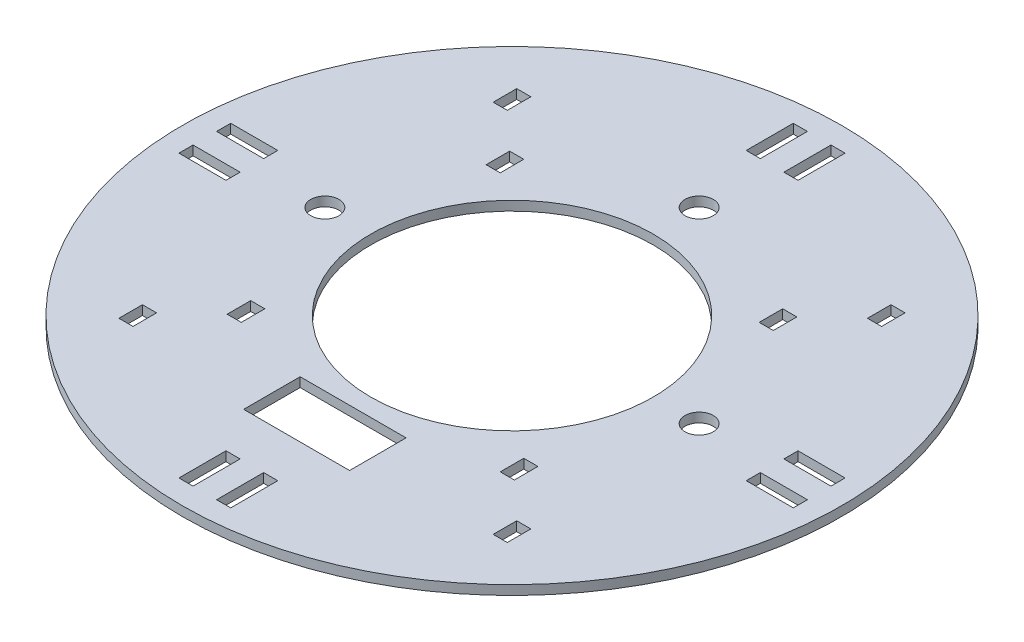
SolidWorks part; units mm, degrees
material "Thornel Mat VMA"
ref_plane "Front Plane" through (0, 0, 0) normal (0, 0, 1) x (1, 0, 0)
ref_plane "Top Plane" through (0, 0, 0) normal (0, 1, 0) x (1, 0, 0)
ref_plane "Right Plane" through (0, 0, 0) normal (1, 0, 0) x (0, 0, -1)
sketch "Sketch1" plane through (0, 0, 0) normal (0, 1, 0) x (1, 0, 0)
  line L0 (-49.4975, 49.4975) -> (-30, 30) construction
  line L1 (-52.2487, 5) -> (-67.2487, 5) construction
  line L2 (-67.2487, 5) -> (-67.2487, -5) construction
  line L3 (-67.2487, -5) -> (-52.2487, -5) construction
  line L4 (-52.2487, -5) -> (-52.2487, 5) construction
  line L5 (-30, -30) -> (30, 30) construction
  line L6 (-30, 30) -> (30, -30) construction
  line L7 (-30, 30) -> (-28, 30)
  line L8 (-30, 30) -> (-30, 25)
  line L9 (-30, 25) -> (-28, 25)
  line L10 (-28, 30) -> (-28, 25)
  line L11 (30, 30) -> (28, 30)
  line L12 (30, 30) -> (30, 25)
  line L13 (30, 25) -> (28, 25)
  line L14 (28, 30) -> (28, 25)
  line L15 (-30, -30) -> (-28, -30)
  line L16 (-30, -30) -> (-30, -25)
  line L17 (-30, -25) -> (-28, -25)
  line L18 (-28, -30) -> (-28, -25)
  line L19 (30, -30) -> (28, -30)
  line L20 (30, -30) -> (30, -25)
  line L21 (30, -25) -> (28, -25)
  line L22 (28, -30) -> (28, -25)
  line L23 (30, 30) -> (49.4975, 49.4975) construction
  line L24 (-49.4975, -49.4975) -> (-30, -30) construction
  line L25 (-30, -30) -> (-30, 30) construction
  line L26 (-30, 30) -> (30, 30) construction
  line L27 (30, 30) -> (30, -30) construction
  line L28 (30, -30) -> (30.057, -29.7836) construction
  line L29 (49.4975, -49.4975) -> (30, -30) construction
  line L30 (0, 49.4975) -> (0, 70) construction
  line L31 (-40.7487, 42.2487) -> (-38.7487, 42.2487)
  line L32 (-40.7487, 42.2487) -> (-40.7487, 37.2487)
  line L33 (-40.7487, 37.2487) -> (-38.7487, 37.2487)
  line L34 (-38.7487, 42.2487) -> (-38.7487, 37.2487)
  line L35 (-40.7487, 42.2487) -> (-38.7487, 37.2487) construction
  line L36 (-40.7487, 37.2487) -> (-38.7487, 42.2487) construction
  line L37 (38.7487, 42.2487) -> (40.7487, 42.2487)
  line L38 (38.7487, 42.2487) -> (38.7487, 37.2487)
  line L39 (38.7487, 37.2487) -> (40.7487, 37.2487)
  line L40 (40.7487, 42.2487) -> (40.7487, 37.2487)
  line L41 (38.7487, 42.2487) -> (40.7487, 37.2487) construction
  line L42 (38.7487, 37.2487) -> (40.7487, 42.2487) construction
  line L43 (38.7487, -37.2487) -> (40.7487, -37.2487)
  line L44 (38.7487, -37.2487) -> (38.7487, -42.2487)
  line L45 (38.7487, -42.2487) -> (40.7487, -42.2487)
  line L46 (40.7487, -37.2487) -> (40.7487, -42.2487)
  line L47 (38.7487, -37.2487) -> (40.7487, -42.2487) construction
  line L48 (38.7487, -42.2487) -> (40.7487, -37.2487) construction
  line L49 (-40.7487, -37.2487) -> (-38.7487, -37.2487)
  line L50 (-40.7487, -37.2487) -> (-40.7487, -42.2487)
  line L51 (-40.7487, -42.2487) -> (-38.7487, -42.2487)
  line L52 (-38.7487, -37.2487) -> (-38.7487, -42.2487)
  line L53 (-40.7487, -37.2487) -> (-38.7487, -42.2487) construction
  line L54 (-40.7487, -42.2487) -> (-38.7487, -37.2487) construction
  line L55 (-49.4975, 0) -> (-70, 0) construction
  line L56 (49.4975, 0) -> (70, 0) construction
  line L57 (0, -49.4975) -> (0, -70) construction
  line L58 (-49.4975, 0) -> (-30, 0) construction
  line L60 (-11.25, -33.7487) -> (11.25, -33.7487)
  line L61 (-11.25, -33.7487) -> (-11.25, -45.7487)
  line L62 (-11.25, -45.7487) -> (11.25, -45.7487)
  line L63 (-5, 52.2487) -> (5, 67.2487) construction
  line L64 (-5, 67.2487) -> (5, 52.2487) construction
  line L65 (-5, 52.2487) -> (5, 52.2487) construction
  line L66 (5, 52.2487) -> (5, 67.2487) construction
  line L67 (5, 67.2487) -> (-5, 67.2487) construction
  line L68 (-5, 67.2487) -> (-5, 52.2487) construction
  line L69 (52.2487, -5) -> (67.2487, 5) construction
  line L70 (52.2487, 5) -> (67.2487, -5) construction
  line L71 (52.2487, -5) -> (67.2487, -5) construction
  line L72 (67.2487, -5) -> (67.2487, 5) construction
  line L73 (67.2487, 5) -> (52.2487, 5) construction
  line L74 (52.2487, 5) -> (52.2487, -5) construction
  line L75 (-5, -52.2487) -> (5, -67.2487) construction
  line L76 (-5, -67.2487) -> (5, -52.2487) construction
  line L77 (-5, -52.2487) -> (5, -52.2487) construction
  line L78 (5, -52.2487) -> (5, -67.2487) construction
  line L79 (5, -67.2487) -> (-5, -67.2487) construction
  line L80 (-5, -67.2487) -> (-5, -52.2487) construction
  line L81 (-67.2487, 5) -> (-52.2487, -5) construction
  line L82 (-67.2487, -5) -> (-52.2487, 5) construction
  line L83 (-67.2487, 5) -> (-62.2487, 5)
  line L84 (-67.2487, 5) -> (-67.2487, 3)
  line L85 (-67.2487, 3) -> (-62.2487, 3)
  line L86 (-62.2487, 5) -> (-62.2487, 3)
  line L87 (-67.2487, -5) -> (-62.2487, -5)
  line L88 (-67.2487, -5) -> (-67.2487, -3)
  line L89 (-67.2487, -3) -> (-62.2487, -3)
  line L90 (-62.2487, -5) -> (-62.2487, -3)
  line L91 (-52.2487, -5) -> (-57.2487, -5)
  line L92 (-52.2487, -5) -> (-52.2487, -3)
  line L93 (-52.2487, -3) -> (-57.2487, -3)
  line L94 (-57.2487, -5) -> (-57.2487, -3)
  line L95 (-52.2487, 5) -> (-57.2487, 5)
  line L96 (-52.2487, 5) -> (-52.2487, 3)
  line L97 (-52.2487, 3) -> (-57.2487, 3)
  line L98 (-57.2487, 5) -> (-57.2487, 3)
  line L99 (-5, 67.2487) -> (-3, 67.2487)
  line L100 (-5, 67.2487) -> (-5, 62.2487)
  line L101 (-5, 62.2487) -> (-3, 62.2487)
  line L102 (-3, 67.2487) -> (-3, 62.2487)
  line L103 (-5, 52.2487) -> (-3, 52.2487)
  line L104 (-5, 52.2487) -> (-5, 57.2487)
  line L105 (-5, 57.2487) -> (-3, 57.2487)
  line L106 (-3, 52.2487) -> (-3, 57.2487)
  line L107 (5, 52.2487) -> (3, 52.2487)
  line L108 (5, 52.2487) -> (5, 57.2487)
  line L109 (5, 57.2487) -> (3, 57.2487)
  line L110 (3, 52.2487) -> (3, 57.2487)
  line L111 (5, 67.2487) -> (3, 67.2487)
  line L112 (5, 67.2487) -> (5, 62.2487)
  line L113 (5, 62.2487) -> (3, 62.2487)
  line L114 (3, 67.2487) -> (3, 62.2487)
  line L115 (52.2487, 5) -> (57.2487, 5)
  line L116 (52.2487, 5) -> (52.2487, 3)
  line L117 (52.2487, 3) -> (57.2487, 3)
  line L118 (57.2487, 5) -> (57.2487, 3)
  line L119 (52.2487, -5) -> (57.2487, -5)
  line L120 (52.2487, -5) -> (52.2487, -3)
  line L121 (52.2487, -3) -> (57.2487, -3)
  line L122 (57.2487, -5) -> (57.2487, -3)
  line L123 (67.2487, 5) -> (62.2487, 5)
  line L124 (67.2487, 5) -> (67.2487, 3)
  line L125 (67.2487, 3) -> (62.2487, 3)
  line L126 (62.2487, 5) -> (62.2487, 3)
  line L127 (67.2487, -5) -> (62.2487, -5)
  line L128 (67.2487, -5) -> (67.2487, -3)
  line L129 (67.2487, -3) -> (62.2487, -3)
  line L130 (62.2487, -5) -> (62.2487, -3)
  line L131 (-5, -52.2487) -> (-3, -52.2487)
  line L132 (-5, -52.2487) -> (-5, -57.2487)
  line L133 (-5, -57.2487) -> (-3, -57.2487)
  line L134 (-3, -52.2487) -> (-3, -57.2487)
  line L135 (5, -52.2487) -> (3, -52.2487)
  line L136 (5, -52.2487) -> (5, -57.2487)
  line L137 (5, -57.2487) -> (3, -57.2487)
  line L138 (3, -52.2487) -> (3, -57.2487)
  line L139 (5, -67.2487) -> (3, -67.2487)
  line L140 (5, -67.2487) -> (5, -62.2487)
  line L141 (5, -62.2487) -> (3, -62.2487)
  line L142 (3, -67.2487) -> (3, -62.2487)
  line L143 (-5, -67.2487) -> (-3, -67.2487)
  line L144 (-5, -67.2487) -> (-5, -62.2487)
  line L145 (-5, -62.2487) -> (-3, -62.2487)
  line L146 (-3, -67.2487) -> (-3, -62.2487)
  line L147 (0, 49.4975) -> (0, 30) construction
  line L148 (30, 0) -> (49.4975, 0) construction
  line L149 (0, -30) -> (0, -49.4975) construction
  line L150 (-49.4975, -49.4975) -> (-49.4975, 49.4975) construction
  line L151 (-49.4975, 49.4975) -> (49.4975, 49.4975) construction
  line L152 (49.4975, 49.4975) -> (49.4975, -49.4975) construction
  line L153 (49.4975, -49.4975) -> (-49.4975, -49.4975) construction
  line L154 (-30, -30) -> (30, -30) construction
  line L155 (-52.2487, 5) -> (-67.2487, 5) construction
  line L156 (11.25, -33.7487) -> (11.25, -45.7487)
  line L157 (-11.25, -33.7487) -> (11.25, -45.7487) construction
  line L158 (-11.25, -45.7487) -> (11.25, -33.7487) construction
  circle A0 centre (0, 0) radius 30
  circle A1 centre (0, 0) radius 70
  circle A2 centre (0, -39.7487) radius 3
  circle A3 centre (39.7487, 0) radius 3
  circle A4 centre (-39.7487, 0) radius 3
  circle A5 centre (0, 39.7487) radius 3
  point P20 (-39.7487, 39.7487)
  point P29 (39.7487, 39.7487)
  point P34 (39.7487, -39.7487)
  point P39 (-39.7487, -39.7487)
  point P52 (0, 59.7487)
  point P57 (59.7487, 0)
  point P62 (0, -59.7487)
  point P67 (-59.7487, 0)
  dimension "D1" = 60
  dimension "D2" = 140
  dimension "D65" = 6
  dimension "D66" = 6
  dimension "D67" = 6
  dimension "D68" = 6
  dimension "D3" = 60
  dimension "D4" = 60
  dimension "D5" = 5
  dimension "D6" = 2
  dimension "D7" = 5
  dimension "D8" = 2
  dimension "D9" = 2
  dimension "D10" = 5
  dimension "D11" = 2
  dimension "D12" = 5
  dimension "D13" = 5
  dimension "D14" = 2
  dimension "D15" = 5
  dimension "D16" = 2
  dimension "D17" = 2
  dimension "D18" = 5
  dimension "D19" = 2
  dimension "D20" = 5
  dimension "D21" = 20.5025
  dimension "D22" = 15
  dimension "D23" = 10
  dimension "D24" = 20.5025
  dimension "D25" = 15
  dimension "D26" = 10
  dimension "D27" = 20.5025
  dimension "D28" = 15
  dimension "D29" = 10
  dimension "D30" = 20.5025
  dimension "D31" = 15
  dimension "D32" = 10
  dimension "D33" = 5
  dimension "D34" = 2
  dimension "D35" = 5
  dimension "D36" = 2
  dimension "D37" = 5
  dimension "D38" = 2
  dimension "D39" = 5
  dimension "D40" = 5
  dimension "D41" = 5
  dimension "D42" = 5
  dimension "D43" = 5
  dimension "D44" = 2
  dimension "D45" = 2
  dimension "D46" = 2
  dimension "D47" = 2
  dimension "D48" = 5
  dimension "D49" = 5
  dimension "D50" = 5
  dimension "D51" = 5
  dimension "D52" = 2
  dimension "D53" = 2
  dimension "D54" = 2
  dimension "D55" = 2
  dimension "D56" = 2
  dimension "D57" = 5
  dimension "D58" = 5
  dimension "D59" = 2
  dimension "D60" = 2
  dimension "D61" = 2
  dimension "D62" = 5
  dimension "D63" = 5
  dimension "D64" = 2
  dimension "D69" = 19.4975
  dimension "D70" = 22.5
  dimension "D71" = 12
extrude "Yükseklik-Ekstrüzyon1" add sketch "Sketch1" along normal blind 2 contours A1 A5 A4 A3 L60 L156 L62 L61 L146 L143 L144 L145 L131 L134 L133 L132 L115 L118 L117 L116 L114 L111 L112 L113 L99 L102 L101 L100 L98 L95 L96 L97 L83 L86 L85 L84 L43 L46 L45
sketch "Sketch2" plane through (0, 2, 0) normal (0, 1, 0) x (1, 0, 0)
  line L0 (-52.2487, 5) -> (-52.2487, 21.5478)
  line L1 (-52.2487, 21.5478) -> (-52.2487, -8.4522)
  dimension "D1" = 30
sketch "Sketch3" plane through (0, 2, 0) normal (0, 1, 0) x (1, 0, 0)
  line L0 (-65.2487, 5) -> (-55.2487, 5)
  line L1 (-67.2487, 5) -> (-62.2487, 5) construction
  line L2 (-52.2487, 5) -> (-57.2487, 5) construction
  line L3 (-65.2487, 3) -> (-55.2487, 3)
  line L4 (-67.2487, 3) -> (-62.2487, 3) construction
  line L5 (-52.2487, 3) -> (-57.2487, 3) construction
  line L6 (-55.2487, 3) -> (-55.2487, 5)
  line L7 (-55.2487, 5) -> (-55.2081, 4.9702)
  line L8 (-65.2487, 3) -> (-65.2487, 5)
  line L10 (-55.2487, 5) -> (-52.2487, 5)
  line L11 (-55.2487, 5) -> (-55.2487, 3)
  line L12 (-55.2487, 3) -> (-52.2487, 3)
  line L13 (-52.2487, 5) -> (-52.2487, 3)
  line L14 (-65.2487, 5) -> (-67.2487, 5)
  line L15 (-65.2487, 5) -> (-65.2487, 3)
  line L16 (-65.2487, 3) -> (-67.2487, 3)
  line L17 (-67.2487, 5) -> (-67.2487, 3)
  dimension "D1" = 2
  dimension "D2" = 10
extrude "Boss-Extrude1" add sketch "Sketch3" against normal blind 2
sketch "Sketch5" plane through (0, 2, 0) normal (0, 1, 0) x (1, 0, 0)
  line L1 (-62.2487, 5) -> (-57.2487, 5)
  line L2 (-62.2487, 5) -> (-62.2487, 3)
  line L3 (-62.2487, 3) -> (-57.2487, 3)
  line L4 (-57.2487, 5) -> (-57.2487, 3)
extrude "Cut-Extrude1" cut sketch "Sketch5" against normal blind 2
sketch "Sketch6" plane through (0, 2, 0) normal (0, 1, 0) x (1, 0, 0)
  line L0 (-67.2487, -3) -> (-62.2487, -3) construction
  line L1 (-65.2487, -3) -> (-55.2487, -3)
  line L2 (-65.2487, -3) -> (-65.2487, -5)
  line L3 (-65.2487, -5) -> (-55.2487, -5)
  line L4 (-55.2487, -3) -> (-55.2487, -5)
  line L5 (-52.2487, -5) -> (-57.2487, -5) construction
  line L6 (-67.2487, -5) -> (-67.2487, -3) construction
  line L8 (-65.2487, -3) -> (-67.2487, -3)
  line L9 (-65.2487, -3) -> (-65.2487, -5)
  line L10 (-65.2487, -5) -> (-67.2487, -5)
  line L11 (-67.2487, -3) -> (-67.2487, -5)
  line L12 (-55.2487, -3) -> (-52.2487, -3)
  line L13 (-55.2487, -3) -> (-55.2487, -5)
  line L14 (-55.2487, -5) -> (-52.2487, -5)
  line L15 (-52.2487, -3) -> (-52.2487, -5)
  dimension "D1" = 10
  dimension "D2" = 2
extrude "Boss-Extrude3" add sketch "Sketch6" against normal blind 2 contours L8 L11 L10 L2 | L15 L12 L4 L14
sketch "Sketch8" plane through (0, 2, 0) normal (0, 1, 0) x (1, 0, 0)
  line L1 (-62.2487, -3) -> (-57.2487, -3)
  line L2 (-62.2487, -3) -> (-62.2487, -5)
  line L3 (-62.2487, -5) -> (-57.2487, -5)
  line L4 (-57.2487, -3) -> (-57.2487, -5)
extrude "Cut-Extrude2" cut sketch "Sketch8" against normal blind 2
sketch "Sketch9" plane through (0, 2, 0) normal (0, 1, 0) x (1, 0, 0)
  line L0 (3, 67.2487) -> (3, 62.2487) construction
  line L1 (3, 65.2487) -> (5, 65.2487)
  line L2 (3, 65.2487) -> (3, 55.2487)
  line L3 (3, 55.2487) -> (5, 55.2487)
  line L4 (5, 65.2487) -> (5, 55.2487)
  line L5 (5, 52.2487) -> (5, 57.2487) construction
  line L6 (5, 67.2487) -> (3, 67.2487) construction
  line L8 (5, 55.2487) -> (3, 55.2487)
  line L9 (5, 55.2487) -> (5, 52.2487)
  line L10 (5, 52.2487) -> (3, 52.2487)
  line L11 (3, 55.2487) -> (3, 52.2487)
  line L12 (5, 65.2487) -> (3, 65.2487)
  line L13 (5, 65.2487) -> (5, 67.2487)
  line L14 (5, 67.2487) -> (3, 67.2487)
  line L15 (3, 65.2487) -> (3, 67.2487)
  dimension "D1" = 2
  dimension "D2" = 10
extrude "Boss-Extrude4" add sketch "Sketch9" against normal blind 2 contours L15 L1 L13 L14 | L3 L11 L10 L9
sketch "Sketch10" plane through (0, 2, 0) normal (0, 1, 0) x (1, 0, 0)
  line L0 (-5, 67.2487) -> (-5, 62.2487) construction
  line L1 (3, 62.2487) -> (5, 62.2487)
  line L2 (3, 62.2487) -> (3, 57.2487)
  line L3 (3, 57.2487) -> (5, 57.2487)
  line L4 (5, 62.2487) -> (5, 57.2487)
  line L5 (-5, 65.2487) -> (-3, 65.2487)
  line L6 (-5, 65.2487) -> (-5, 55.2487)
  line L7 (-5, 55.2487) -> (-3, 55.2487)
  line L8 (-3, 65.2487) -> (-3, 55.2487)
  line L9 (-3, 52.2487) -> (-3, 57.2487) construction
  line L10 (-5, 67.2487) -> (-3, 67.2487) construction
  line L12 (-3, 55.2487) -> (-5, 55.2487)
  line L13 (-3, 55.2487) -> (-3, 52.2487)
  line L14 (-3, 52.2487) -> (-5, 52.2487)
  line L15 (-5, 55.2487) -> (-5, 52.2487)
  line L16 (-3, 65.2487) -> (-5, 65.2487)
  line L17 (-3, 65.2487) -> (-3, 67.2487)
  line L18 (-3, 67.2487) -> (-5, 67.2487)
  line L19 (-5, 65.2487) -> (-5, 67.2487)
  dimension "D1" = 2
  dimension "D2" = 10
extrude "Boss-Extrude5" add sketch "Sketch10" against normal blind 2 contours L19 L5 L17 L18 | L7 L15 L14 L13
sketch "Sketch12" plane through (0, 2, 0) normal (0, 1, 0) x (1, 0, 0)
  line L1 (-5, 62.2487) -> (-3, 62.2487)
  line L2 (-5, 62.2487) -> (-5, 57.2487)
  line L3 (-5, 57.2487) -> (-3, 57.2487)
  line L4 (-3, 62.2487) -> (-3, 57.2487)
extrude "Cut-Extrude4" cut sketch "Sketch12" against normal blind 2
sketch "Sketch13" plane through (0, 2, 0) normal (0, 1, 0) x (1, 0, 0)
  line L1 (5, 62.2487) -> (3, 62.2487)
  line L2 (5, 62.2487) -> (5, 57.2487)
  line L3 (5, 57.2487) -> (3, 57.2487)
  line L4 (3, 62.2487) -> (3, 57.2487)
extrude "Cut-Extrude5" cut sketch "Sketch13" against normal blind 2
sketch "Sketch14" plane through (0, 2, 0) normal (0, 1, 0) x (1, 0, 0)
  line L0 (67.2487, 5) -> (62.2487, 5) construction
  line L1 (65.2487, 5) -> (55.2487, 5)
  line L2 (65.2487, 5) -> (65.2487, 3)
  line L3 (65.2487, 3) -> (55.2487, 3)
  line L4 (55.2487, 5) -> (55.2487, 3)
  line L5 (52.2487, 3) -> (57.2487, 3) construction
  line L6 (67.2487, 5) -> (67.2487, 3) construction
  line L8 (52.2487, 5) -> (55.2487, 5)
  line L9 (52.2487, 5) -> (52.2487, 3)
  line L10 (52.2487, 3) -> (55.2487, 3)
  line L11 (55.2487, 5) -> (55.2487, 3)
  line L12 (65.2487, 5) -> (67.2487, 5)
  line L13 (65.2487, 5) -> (65.2487, 3)
  line L14 (65.2487, 3) -> (67.2487, 3)
  line L15 (67.2487, 5) -> (67.2487, 3)
  dimension "D1" = 2
  dimension "D2" = 10
extrude "Boss-Extrude6" add sketch "Sketch14" against normal blind 2 contours L9 L10 L4 L8 | L15 L12 L2 L14
sketch "Sketch15" plane through (0, 2, 0) normal (0, 1, 0) x (1, 0, 0)
  line L1 (57.2487, 5) -> (62.2487, 5)
  line L2 (57.2487, 5) -> (57.2487, 3)
  line L3 (57.2487, 3) -> (62.2487, 3)
  line L4 (62.2487, 5) -> (62.2487, 3)
extrude "Cut-Extrude6" cut sketch "Sketch15" against normal blind 2
sketch "Sketch16" plane through (0, 2, 0) normal (0, 1, 0) x (1, 0, 0)
  line L0 (67.2487, -3) -> (62.2487, -3) construction
  line L1 (65.2487, -3) -> (55.2487, -3)
  line L2 (65.2487, -3) -> (65.2487, -5)
  line L3 (65.2487, -5) -> (55.2487, -5)
  line L4 (55.2487, -3) -> (55.2487, -5)
  line L5 (52.2487, -5) -> (57.2487, -5) construction
  line L6 (67.2487, -5) -> (67.2487, -3) construction
  line L8 (65.2487, -3) -> (67.2487, -3)
  line L9 (65.2487, -3) -> (65.2487, -5)
  line L10 (65.2487, -5) -> (67.2487, -5)
  line L11 (67.2487, -3) -> (67.2487, -5)
  line L12 (55.2487, -3) -> (52.2487, -3)
  line L13 (55.2487, -3) -> (55.2487, -5)
  line L14 (55.2487, -5) -> (52.2487, -5)
  line L15 (52.2487, -3) -> (52.2487, -5)
  dimension "D1" = 2
  dimension "D2" = 10
extrude "Boss-Extrude9" add sketch "Sketch16" against normal blind 2 contours L12 L15 L14 L4 | L11 L8 L2 L10
sketch "Sketch17" plane through (0, 2, 0) normal (0, 1, 0) x (1, 0, 0)
  line L1 (57.2487, -3) -> (62.2487, -3)
  line L2 (57.2487, -3) -> (57.2487, -5)
  line L3 (57.2487, -5) -> (62.2487, -5)
  line L4 (62.2487, -3) -> (62.2487, -5)
extrude "Cut-Extrude7" cut sketch "Sketch17" against normal blind 2
sketch "Sketch18" plane through (0, 2, 0) normal (0, 1, 0) x (1, 0, 0)
  line L0 (-5, -67.2487) -> (-3, -67.2487) construction
  line L1 (3, -52.2487) -> (3, -57.2487) construction
  line L2 (3, -55.2487) -> (5, -55.2487)
  line L3 (3, -55.2487) -> (3, -65.2487)
  line L4 (3, -65.2487) -> (5, -65.2487)
  line L6 (-5, -52.2487) -> (-3, -52.2487)
  line L7 (-5, -67.2487) -> (-5, -62.2487) construction
  line L8 (-5, -65.2487) -> (-3, -65.2487)
  line L9 (-5, -65.2487) -> (-5, -55.2487)
  line L10 (-5, -55.2487) -> (-3, -55.2487)
  line L11 (-5, -52.2487) -> (-5, -55.2487)
  line L12 (-5, -55.2487) -> (-3, -55.2487)
  line L13 (-3, -52.2487) -> (-3, -55.2487)
  line L14 (5, -55.2487) -> (5, -65.2487)
  line L15 (5, -67.2487) -> (5, -62.2487) construction
  line L16 (5, -67.2487) -> (3, -67.2487) construction
  line L17 (-3, -65.2487) -> (-3, -55.2487)
  line L18 (-3, -52.2487) -> (-3, -57.2487) construction
  line L19 (3, -52.2487) -> (5, -52.2487)
  line L20 (3, -52.2487) -> (3, -55.2487)
  line L21 (3, -55.2487) -> (5, -55.2487)
  line L22 (5, -52.2487) -> (5, -55.2487)
  line L23 (5, -67.2487) -> (3, -67.2487)
  line L24 (5, -67.2487) -> (5, -65.2487)
  line L25 (5, -65.2487) -> (3, -65.2487)
  line L26 (3, -67.2487) -> (3, -65.2487)
  line L27 (-3, -67.2487) -> (-5, -67.2487)
  line L28 (-3, -67.2487) -> (-3, -65.2487)
  line L29 (-3, -65.2487) -> (-5, -65.2487)
  line L30 (-5, -67.2487) -> (-5, -65.2487)
  dimension "D1" = 2
  dimension "D2" = 10
  dimension "D3" = 2
  dimension "D4" = 10
extrude "Boss-Extrude10" add sketch "Sketch18" against normal blind 2 contours L13 L6 L11 L10 | L30 L27 L28 L8 | L26 L23 L24 L4 | L22 L19 L20 L2
sketch "Sketch19" plane through (0, 2, 0) normal (0, 1, 0) x (1, 0, 0)
  line L1 (3, -57.2487) -> (5, -57.2487)
  line L2 (3, -57.2487) -> (3, -62.2487)
  line L3 (3, -62.2487) -> (5, -62.2487)
  line L4 (5, -57.2487) -> (5, -62.2487)
  line L5 (-3, -57.2487) -> (-5, -57.2487)
  line L6 (-3, -57.2487) -> (-3, -62.2487)
  line L7 (-3, -62.2487) -> (-5, -62.2487)
  line L8 (-5, -57.2487) -> (-5, -62.2487)
extrude "Cut-Extrude8" cut sketch "Sketch19" against normal blind 2
sketch "Sketch20" plane through (0, 2, 0) normal (0, 1, 0) x (1, 0, 0)
  line L0 (-5, 65.2487) -> (-5, 55.2487) construction
  line L1 (-2.5, 55.2487) -> (-5.5, 55.2487)
  line L2 (-2.5, 55.2487) -> (-2.5, 65.2487)
  line L3 (-2.5, 65.2487) -> (-5.5, 65.2487)
  line L4 (-5.5, 55.2487) -> (-5.5, 65.2487)
  line L5 (3, 65.2487) -> (5, 65.2487) construction
  line L6 (2.5, 65.2487) -> (5.5, 65.2487)
  line L7 (2.5, 65.2487) -> (2.5, 55.2487)
  line L8 (2.5, 55.2487) -> (5.5, 55.2487)
  line L9 (5.5, 65.2487) -> (5.5, 55.2487)
  line L10 (3, 55.2487) -> (5, 55.2487) construction
  line L11 (5, 65.2487) -> (5, 55.2487) construction
  line L12 (55.2487, 5) -> (55.2487, 3) construction
  line L13 (55.2487, 5.5) -> (65.2487, 5.5)
  line L14 (55.2487, 5.5) -> (55.2487, 2.5)
  line L15 (55.2487, 2.5) -> (65.2487, 2.5)
  line L16 (65.2487, 5.5) -> (65.2487, 2.5)
  line L17 (65.2487, 5) -> (65.2487, 3) construction
  line L18 (55.2487, 5) -> (65.2487, 5) construction
  line L19 (55.2487, -3) -> (55.2487, -5) construction
  line L20 (55.2487, -5.5) -> (65.2487, -5.5)
  line L21 (55.2487, -5.5) -> (55.2487, -2.5)
  line L22 (55.2487, -2.5) -> (65.2487, -2.5)
  line L23 (65.2487, -5.5) -> (65.2487, -2.5)
  line L24 (65.2487, -3) -> (65.2487, -5) construction
  line L25 (55.2487, -3) -> (65.2487, -3) construction
  line L26 (3, -55.2487) -> (5, -55.2487) construction
  line L27 (2.5, -55.2487) -> (5.5, -55.2487)
  line L28 (2.5, -55.2487) -> (2.5, -65.2487)
  line L29 (2.5, -65.2487) -> (5.5, -65.2487)
  line L30 (5.5, -55.2487) -> (5.5, -65.2487)
  line L31 (3, -65.2487) -> (5, -65.2487) construction
  line L32 (5, -65.2487) -> (5, -55.2487) construction
  line L33 (-5, -55.2487) -> (-3, -55.2487) construction
  line L34 (-5.5, -55.2487) -> (-2.5, -55.2487)
  line L35 (-5.5, -55.2487) -> (-5.5, -65.2487)
  line L36 (-5.5, -65.2487) -> (-2.5, -65.2487)
  line L37 (-2.5, -55.2487) -> (-2.5, -65.2487)
  line L38 (-5, -65.2487) -> (-3, -65.2487) construction
  line L39 (-3, -55.2487) -> (-3, -65.2487) construction
  line L40 (-65.2487, 3) -> (-65.2487, 5) construction
  line L41 (-65.2487, 5.5) -> (-55.2487, 5.5)
  line L42 (-65.2487, 5.5) -> (-65.2487, 2.5)
  line L43 (-65.2487, 2.5) -> (-55.2487, 2.5)
  line L44 (-55.2487, 5.5) -> (-55.2487, 2.5)
  line L45 (-55.2487, 3) -> (-55.2487, 5) construction
  line L46 (-65.2487, 5) -> (-55.2487, 5) construction
  line L47 (-55.2487, -3) -> (-55.2487, -5) construction
  line L48 (-55.2487, -2.5) -> (-65.2487, -2.5)
  line L49 (-55.2487, -2.5) -> (-55.2487, -5.5)
  line L50 (-55.2487, -5.5) -> (-65.2487, -5.5)
  line L51 (-65.2487, -2.5) -> (-65.2487, -5.5)
  line L52 (-65.2487, -3) -> (-65.2487, -5) construction
  line L53 (-65.2487, -3) -> (-55.2487, -3) construction
  line L54 (-30, 30) -> (-28, 30) construction
  line L55 (-30.5, 30) -> (-27.5, 30)
  line L56 (-30.5, 30) -> (-30.5, 25)
  line L57 (-30.5, 25) -> (-27.5, 25)
  line L58 (-27.5, 30) -> (-27.5, 25)
  line L59 (-30, 25) -> (-28, 25) construction
  line L60 (-28, 30) -> (-28, 25) construction
  line L61 (-40.7487, 42.2487) -> (-38.7487, 42.2487) construction
  line L62 (-41.2487, 42.2487) -> (-38.2487, 42.2487)
  line L63 (-41.2487, 42.2487) -> (-41.2487, 37.2487)
  line L64 (-41.2487, 37.2487) -> (-38.2487, 37.2487)
  line L65 (-38.2487, 42.2487) -> (-38.2487, 37.2487)
  line L66 (-40.7487, 37.2487) -> (-38.7487, 37.2487) construction
  line L67 (-38.7487, 42.2487) -> (-38.7487, 37.2487) construction
  line L68 (30, 30) -> (28, 30) construction
  line L69 (27.5, 30) -> (30.5, 30)
  line L70 (27.5, 30) -> (27.5, 25)
  line L71 (27.5, 25) -> (30.5, 25)
  line L72 (30.5, 30) -> (30.5, 25)
  line L73 (30, 25) -> (28, 25) construction
  line L74 (30, 30) -> (30, 25) construction
  line L75 (38.7487, 42.2487) -> (40.7487, 42.2487) construction
  line L76 (38.2487, 42.2487) -> (41.2487, 42.2487)
  line L77 (38.2487, 42.2487) -> (38.2487, 37.2487)
  line L78 (38.2487, 37.2487) -> (41.2487, 37.2487)
  line L79 (41.2487, 42.2487) -> (41.2487, 37.2487)
  line L80 (38.7487, 37.2487) -> (40.7487, 37.2487) construction
  line L81 (40.7487, 42.2487) -> (40.7487, 37.2487) construction
  line L82 (30, -25) -> (28, -25) construction
  line L83 (27.5, -25) -> (30.5, -25)
  line L84 (27.5, -25) -> (27.5, -30)
  line L85 (27.5, -30) -> (30.5, -30)
  line L86 (30.5, -25) -> (30.5, -30)
  line L87 (30, -30) -> (28, -30) construction
  line L88 (30, -30) -> (30, -25) construction
  line L89 (38.7487, -37.2487) -> (40.7487, -37.2487) construction
  line L90 (38.2487, -37.2487) -> (41.2487, -37.2487)
  line L91 (38.2487, -37.2487) -> (38.2487, -42.2487)
  line L92 (38.2487, -42.2487) -> (41.2487, -42.2487)
  line L93 (41.2487, -37.2487) -> (41.2487, -42.2487)
  line L94 (38.7487, -42.2487) -> (40.7487, -42.2487) construction
  line L95 (40.7487, -37.2487) -> (40.7487, -42.2487) construction
  line L96 (-30, -25) -> (-28, -25) construction
  line L97 (-30.5, -25) -> (-27.5, -25)
  line L98 (-30.5, -25) -> (-30.5, -30)
  line L99 (-30.5, -30) -> (-27.5, -30)
  line L100 (-27.5, -25) -> (-27.5, -30)
  line L101 (-30, -30) -> (-28, -30) construction
  line L102 (-28, -30) -> (-28, -25) construction
  line L103 (-40.7487, -37.2487) -> (-38.7487, -37.2487) construction
  line L104 (-41.2487, -37.2487) -> (-38.2487, -37.2487)
  line L105 (-41.2487, -37.2487) -> (-41.2487, -42.2487)
  line L106 (-41.2487, -42.2487) -> (-38.2487, -42.2487)
  line L107 (-38.2487, -37.2487) -> (-38.2487, -42.2487)
  line L108 (-40.7487, -42.2487) -> (-38.7487, -42.2487) construction
  line L109 (-38.7487, -37.2487) -> (-38.7487, -42.2487) construction
  dimension "D1" = 3
  dimension "D2" = 0.5
  dimension "D3" = 10
  dimension "D4" = 3
  dimension "D5" = 0.5
  dimension "D6" = 3
  dimension "D7" = 0.5
  dimension "D8" = 3
  dimension "D9" = 0.5
  dimension "D10" = 3
  dimension "D11" = 0.5
  dimension "D12" = 3
  dimension "D13" = 0.5
  dimension "D14" = 3
  dimension "D15" = 0.5
  dimension "D16" = 3
  dimension "D17" = 0.5
  dimension "D18" = 3
  dimension "D19" = 0.5
  dimension "D20" = 3
  dimension "D21" = 0.5
  dimension "D22" = 3
  dimension "D23" = 0.5
  dimension "D24" = 3
  dimension "D25" = 0.5
  dimension "D26" = 3
  dimension "D27" = 0.5
  dimension "D28" = 3
  dimension "D29" = 0.5
  dimension "D30" = 3
  dimension "D31" = 0.5
  dimension "D32" = 3
  dimension "D33" = 0.5
extrude "Cut-Extrude9" cut sketch "Sketch20" against normal blind 2
